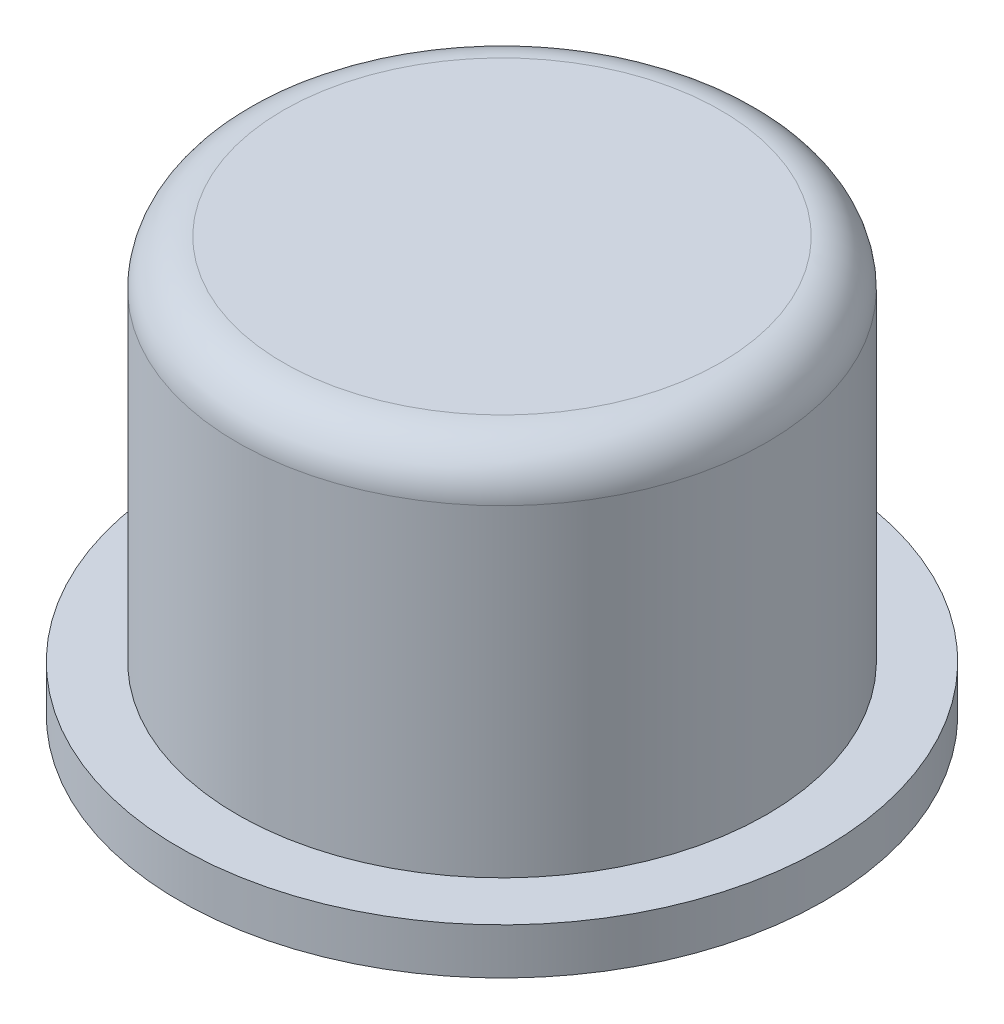
SolidWorks part; units mm, degrees
ref_plane "前视基准面" through (0, 0, 0) normal (0, 0, 1) x (1, 0, 0)
ref_plane "上视基准面" through (0, 0, 0) normal (0, 1, 0) x (1, 0, 0)
ref_plane "右视基准面" through (0, 0, 0) normal (1, 0, 0) x (0, 0, -1)
ref_plane "基准面5" through (0, 0, -3.85) normal (0, 0, 1) x (1, 0, 0)
sketch "草图2" plane through (0, 0, -3.85) normal (0, 0, 1) x (1, 0, 0)
  line L0 (1.9, 3.6) -> (0, 3.6)
  line L1 (0, 3.6) -> (0, 0)
  line L2 (0, 0) -> (2.8, 0)
  line L6 (2.3, 0.4) -> (2.3, 3.2)
  line L7 (0, 3.6) -> (0, 0) construction
  line L9 (2.3, 0.4) -> (2.8, 0.4)
  line L10 (2.8, 0.4) -> (2.8, 0)
  arc A0 (2.3, 3.2) -> (1.9, 3.6) centre (1.9, 3.2) ccw
  dimension "D1" = 0.4
  dimension "D2" = 2.3
  dimension "D4" = 2.8
  dimension "D6" = 0.4
  dimension "D7" = 3.6
revolve "旋转1" add sketch "草图2" angle 360 about L7
sketch "草图5" plane through (0, 0, 0) normal (0, -1, 0) x (1, 0, 0)
  circle A0 centre (0, -3.85) radius 2.8 construction
  circle A1 centre (0, -3.85) radius 2.8 construction
  circle A2 centre (0, -3.85) radius 1.85
  dimension "D1" = 3.7
extrude "切除-拉伸1" cut sketch "草图5" against normal blind 2.8
